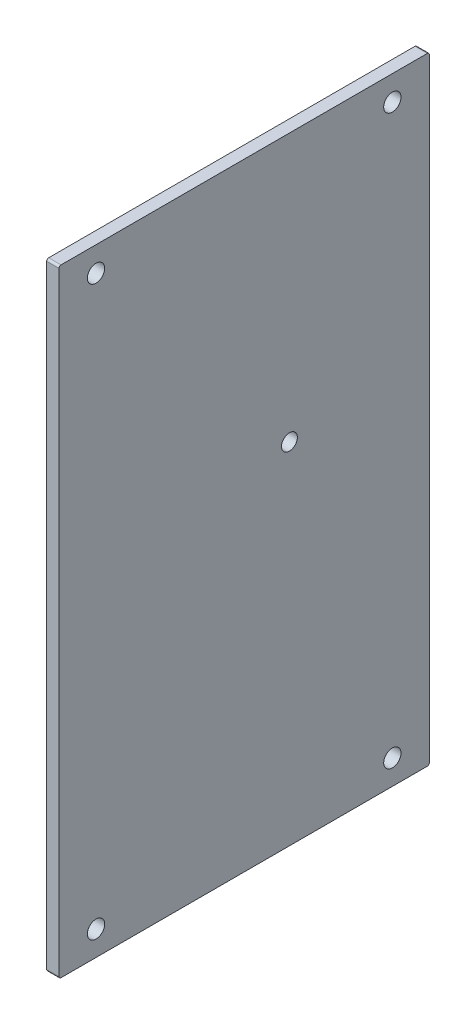
SolidWorks part; units mm, degrees
material "ABS"
ref_plane "Front Plane" through (0, 0, 0) normal (0, 0, 1) x (1, 0, 0)
ref_plane "Top Plane" through (0, 0, 0) normal (0, 1, 0) x (1, 0, 0)
ref_plane "Right Plane" through (0, 0, 0) normal (1, 0, 0) x (0, 0, -1)
sketch "Sketch1" plane through (0, 0, 0) normal (1, 0, 0) x (0, 0, -1)
  line L1 (0, 0) -> (90, 0)
  line L2 (0, 0) -> (0, -150)
  line L3 (0, -150) -> (90, -150)
  line L4 (90, 0) -> (90, -150)
  line L10 (45, 0) -> (45, -70) construction
  circle A0 centre (56, -65) radius 1.925
  circle A8 centre (9, -6) radius 2.1
  circle A9 centre (81, -6) radius 2.1
  circle A10 centre (81, -144) radius 2.1
  circle A11 centre (9, -144) radius 2.1
  point P21 (64.5, -93.5)
  point P26 (49.5, -93.5)
  point P29 (49.5, -85.5)
  dimension "D5" = 3.85
  dimension "D17" = 4.2
  dimension "D3" = 65
  dimension "D14" = 90
  dimension "D2" = 150
  dimension "D15" = 9
  dimension "D16" = 6
  dimension "D4" = 34
  dimension "D6" = 6
  dimension "D7" = 6
extrude "Boss-Extrude1" add sketch "Sketch1" along normal blind 3
fillet "Fillet1" radius 0.5 4 edges at (1.5, -150, -90) (1.5, -150, 0) (1.5, 0, -90) (1.5, 0, 0)
equation "\"Depth\"= 90mm"
equation "\"Height\" = 150mm"
equation "\"Width\"= 64mm"
equation "\"D14@Sketch1\"=\"Depth\""
equation "\"D2@Sketch1\"=\"Height\""
